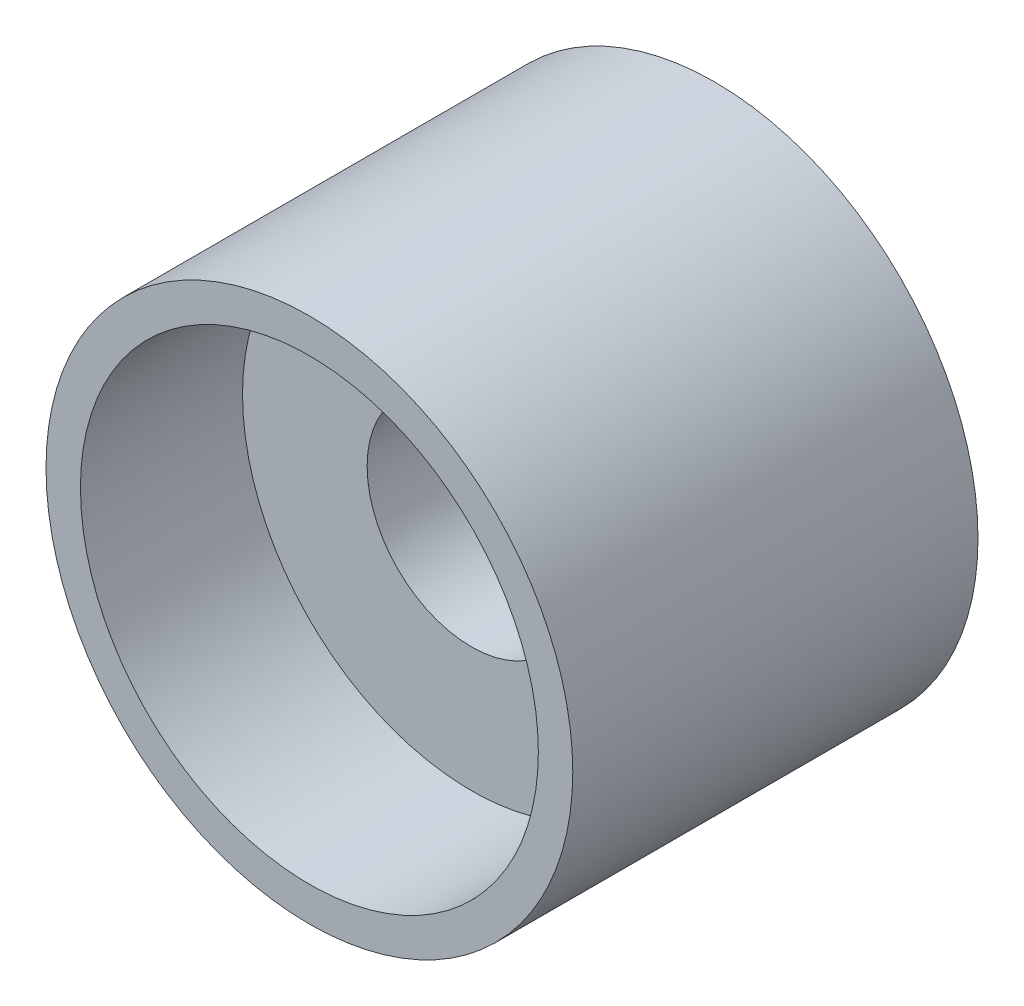
SolidWorks part; units mm, degrees
ref_plane "Front Plane" through (0, 0, 0) normal (0, 0, 1) x (1, 0, 0)
ref_plane "Top Plane" through (0, 0, 0) normal (0, 1, 0) x (1, 0, 0)
ref_plane "Right Plane" through (0, 0, 0) normal (1, 0, 0) x (0, 0, -1)
sketch "Sketch1" plane through (0, 0, 0) normal (0, 0, 1) x (1, 0, 0)
  circle A0 centre (0, 0) radius 13
  circle A1 centre (0, 0) radius 5.15
  dimension "D1" = 26
  dimension "D2" = 10.3
extrude "Boss-Extrude1" add sketch "Sketch1" along normal blind 20
sketch "Sketch2" plane through (0, 0, 20) normal (0, 0, 1) x (1, 0, 0)
  circle A0 centre (0, 0) radius 11.3
  circle A1 centre (0, 0) radius 13 construction
  dimension "D1" = 1.7
extrude "Cut-Extrude1" cut sketch "Sketch2" against normal blind 8
